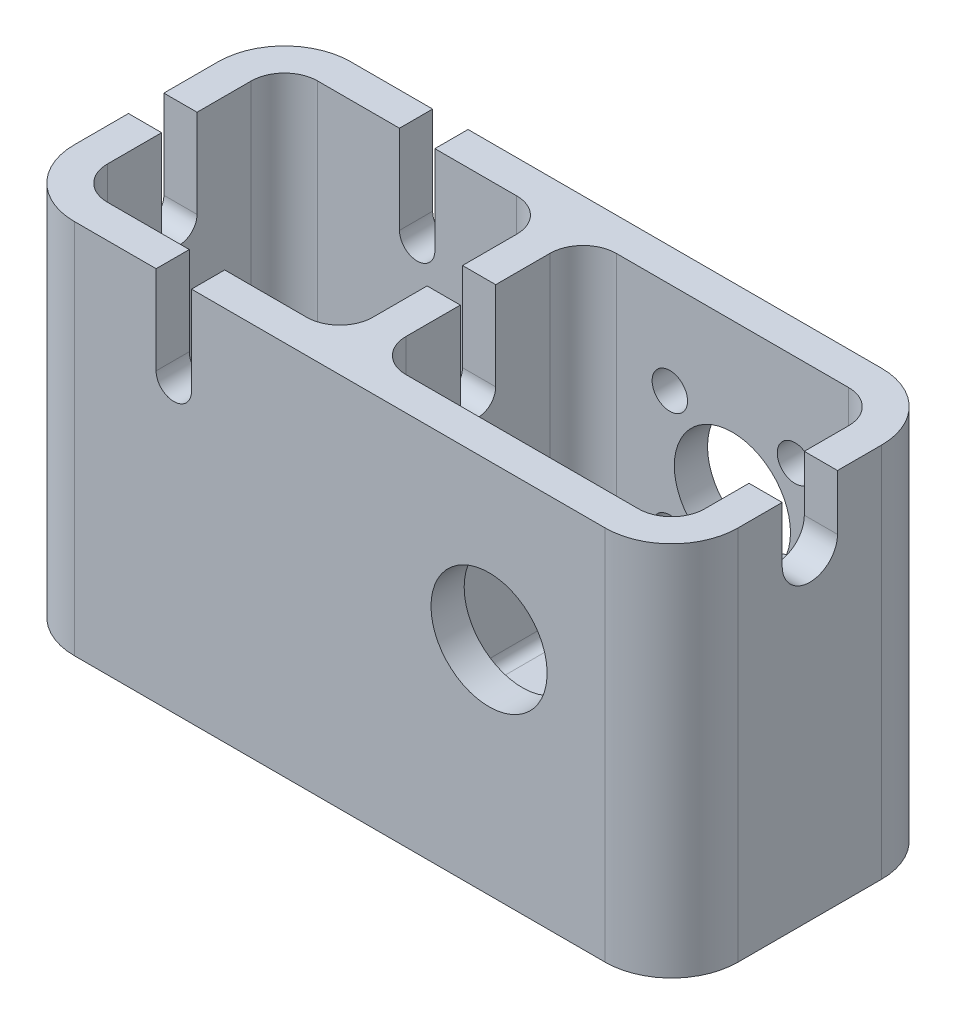
SolidWorks part; units mm, degrees
ref_plane "Front Plane" through (0, 0, 0) normal (0, 0, 1) x (1, 0, 0)
ref_plane "Top Plane" through (0, 0, 0) normal (0, 1, 0) x (1, 0, 0)
ref_plane "Right Plane" through (0, 0, 0) normal (1, 0, 0) x (0, 0, -1)
sketch "Sketch1" plane through (0, 0, 0) normal (0, 1, 0) x (1, 0, 0)
  line L1 (0, 0) -> (60, 0)
  line L2 (0, 0) -> (0, 25)
  line L3 (0, 25) -> (60, 25)
  line L4 (60, 0) -> (60, 25)
  dimension "D1" = 25
  dimension "D2" = 60
extrude "Boss-Extrude1" add sketch "Sketch1" along normal blind 4
sketch "Sketch3" plane through (0, 4, 0) normal (0, 1, 0) x (1, 0, 0)
  line L0 (0, 25) -> (0, 0) construction
  line L1 (60, 25) -> (0, 25) construction
  circle A0 centre (7.5, 17.5) radius 1.6
  circle A1 centre (22.5, 17.5) radius 1.6
  circle A2 centre (22.5, 7.5) radius 1.6
  circle A3 centre (7.5, 7.5) radius 1.6
  dimension "D1" = 3.2
  dimension "D2" = 10
  dimension "D3" = 15
  dimension "D4" = 7.5
  dimension "D5" = 7.5
extrude "Cut-Extrude1" cut sketch "Sketch3" against normal through all
sketch "Sketch4" plane through (0, 4, 0) normal (0, 1, 0) x (1, 0, 0)
  line L0 (27, 22) -> (27, 3)
  line L1 (0, 25) -> (60, 25)
  line L2 (0, 25) -> (0, 0)
  line L3 (0, 0) -> (60, 0)
  line L4 (60, 25) -> (60, 0)
  line L5 (3, 22) -> (27, 22)
  line L6 (3, 22) -> (3, 3)
  line L7 (3, 3) -> (27, 3)
  line L8 (57, 22) -> (57, 3)
  line L9 (30, 22) -> (30, 3)
  line L10 (30, 22) -> (57, 22)
  line L11 (30, 3) -> (57, 3)
  dimension "D1" = 3
  dimension "D2" = 3
  dimension "D3" = 3
  dimension "D4" = 3
  dimension "D5" = 24
  dimension "D6" = 3
extrude "Boss-Extrude2" add sketch "Sketch4" along normal blind 30
sketch "Sketch5" plane through (0, 0, -25) normal (0, 0, -1) x (-1, 0, 0)
  line L0 (-60, 0) -> (0, 0) construction
  line L1 (-57, 34) -> (-30, 34) construction
  circle A0 centre (-43.5, 20) radius 5.25
  point P2 (0, 0)
  point P8 (-43.5, 34)
  dimension "D1" = 10.5
  dimension "D2" = 20
extrude "Cut-Extrude2" cut sketch "Sketch5" against normal through all
sketch "Sketch6" plane through (0, 0, -25) normal (0, 0, -1) x (-1, 0, 0)
  line L0 (-37.8431, 14.3431) -> (-49.1569, 25.6569) construction
  line L1 (-49.1569, 14.3431) -> (-37.8431, 25.6569) construction
  line L2 (-43.5, 14.75) -> (-43.5, 25.25) construction
  line L3 (-38.25, 20) -> (-48.75, 20) construction
  circle A0 centre (-37.8431, 14.3431) radius 1.6
  circle A1 centre (-49.1569, 14.3431) radius 1.6
  circle A2 centre (-49.1569, 25.6569) radius 1.6
  circle A3 centre (-37.8431, 25.6569) radius 1.6
  circle A5 centre (-43.5, 20) radius 5.25 construction
  point P16 (-43.5, 20)
  point P17 (-43.5, 20)
  point P18 (-23.088, 28.9206)
  point P19 (-23.7635, 28.7635)
  dimension "D3" = 3.2
  dimension "D1" = 90
  dimension "D2" = 8
extrude "Cut-Extrude3" cut sketch "Sketch6" against normal up to next
fillet "Fillet3" radius 3 8 edges at (30, 19, -3) (57, 19, -3) (27, 19, -3) (3, 19, -3) (3, 19, -22) (27, 19, -22) (57, 19, -22) (30, 19, -22)
fillet "Fillet4" radius 1 16 edges at (56.1213, 4, -3.8787) (43.5, 4, -3) (30.8787, 4, -3.8787) (30, 4, -12.5) (30.8787, 4, -21.1213) (43.5, 4, -22) (56.1213, 4, -21.1213) (26.1213, 4, -3.8787) (15, 4, -3) (3.8787, 4, -3.8787) (3, 4, -12.5) (3.8787, 4, -21.1213) (15, 4, -22) (26.1213, 4, -21.1213) (57, 4, -12.5) (27, 4, -12.5)
fillet "Fillet5" radius 6 4 edges at (60, 17, 0) (60, 17, -25) (0, 17, 0) (0, 17, -25)
sketch "Sketch7" plane through (0, 0, -25) normal (0, 0, -1) x (-1, 0, 0)
  line L0 (-13.4, 26) -> (-13.4, 34)
  line L1 (-54, 34) -> (-6, 34) construction
  line L2 (-13.4, 34) -> (-16.6, 34)
  line L3 (-16.6, 34) -> (-16.6, 26)
  line L5 (-24, 34) -> (-6, 34) construction
  arc A0 (-16.6, 26) -> (-13.4, 26) centre (-15, 26) ccw
  point P1 (-15, 34)
  point P10 (-15, 34)
  dimension "D1" = 1.6
  dimension "D2" = 8
extrude "Cut-Extrude4" cut sketch "Sketch7" against normal through all
sketch "Sketch8" plane through (0, 0, 0) normal (-1, 0, 0) x (0, 0, 1)
  line L0 (-14.1, 26) -> (-14.1, 34)
  line L1 (-19, 34) -> (-6, 34) construction
  line L2 (-14.1, 34) -> (-10.9, 34)
  line L3 (-10.9, 34) -> (-10.9, 26)
  line L4 (-19, 34) -> (-6, 34) construction
  arc A0 (-14.1, 26) -> (-10.9, 26) centre (-12.5, 26) ccw
  point P1 (-12.5, 34)
  point P10 (-12.5, 34)
  dimension "D2" = 1.6
  dimension "D1" = 8
extrude "Cut-Extrude5" cut sketch "Sketch8" against normal up to surface (30 mm away) up to face at (30, 19.5, -12.5)
sketch "Sketch9" plane through (60, 0, 0) normal (1, 0, 0) x (0, 0, -1)
  line L0 (15, 29) -> (15, 34)
  line L1 (6, 34) -> (19, 34) construction
  line L2 (15, 34) -> (10, 34)
  line L3 (10, 34) -> (10, 29)
  line L4 (6, 34) -> (19, 34) construction
  arc A0 (10, 29) -> (15, 29) centre (12.5, 29) ccw
  point P1 (12.5, 34)
  point P10 (12.5, 34)
  dimension "D2" = 2.5
  dimension "D1" = 5
extrude "Cut-Extrude6" cut sketch "Sketch9" against normal up to next
